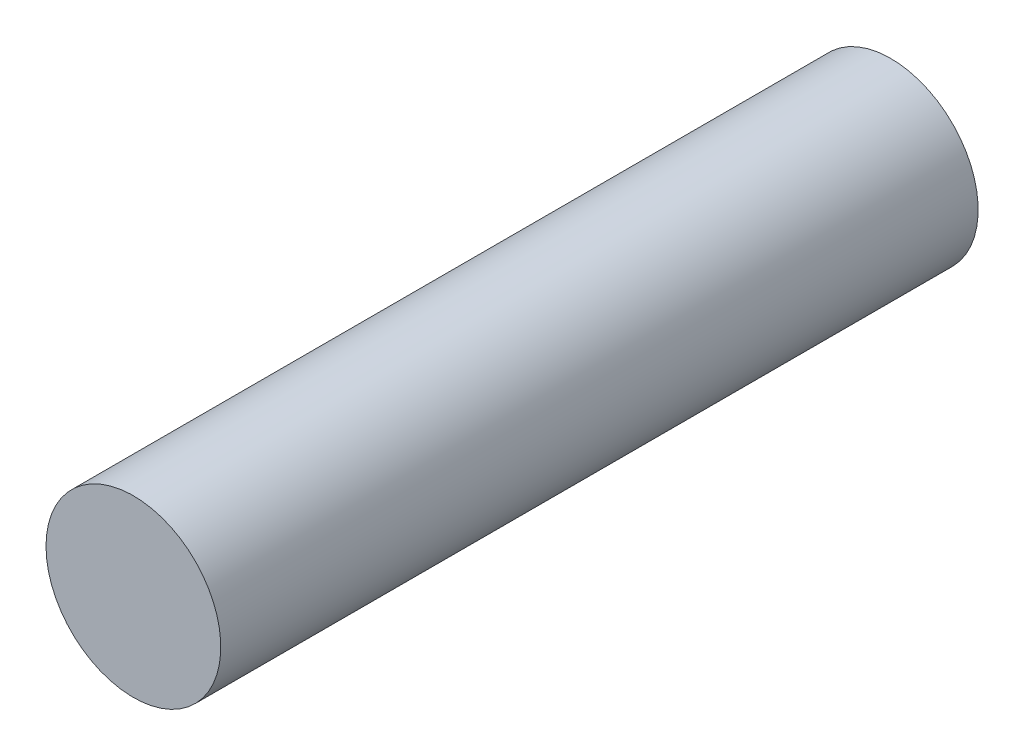
SolidWorks part; units mm, degrees
ref_plane "Ön Düzlem" through (0, 0, 0) normal (0, 0, 1) x (1, 0, 0)
ref_plane "Üst Düzlem" through (0, 0, 0) normal (0, 1, 0) x (1, 0, 0)
ref_plane "Sağ Düzlem" through (0, 0, 0) normal (1, 0, 0) x (0, 0, -1)
sketch "Sketch1" plane through (0, 0, 0) normal (0, 0, 1) x (1, 0, 0)
  circle A0 centre (0, 0) radius 3
  dimension "D1" = 6
extrude "Boss-Extrude1" add sketch "Sketch1" along normal blind 26
